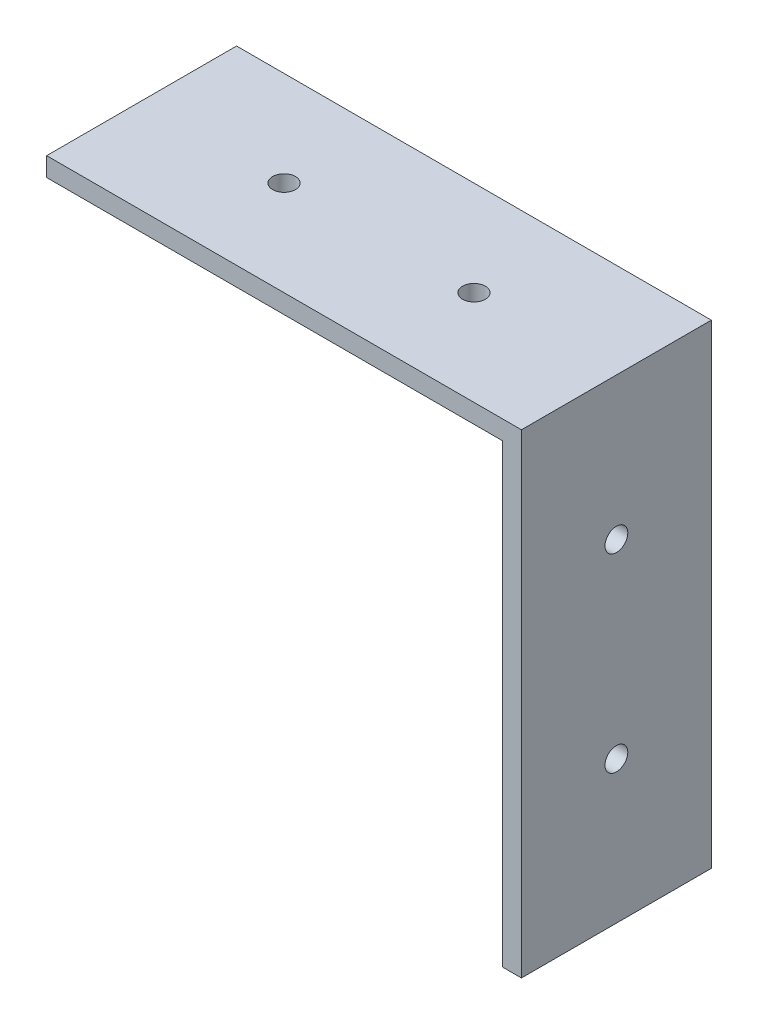
SolidWorks part; units mm, degrees
material "Plain Carbon Steel"
ref_plane "Front Plane" through (0, 0, 0) normal (0, 0, 1) x (1, 0, 0)
ref_plane "Top Plane" through (0, 0, 0) normal (0, 1, 0) x (1, 0, 0)
ref_plane "Right Plane" through (0, 0, 0) normal (1, 0, 0) x (0, 0, -1)
sketch "Sketch1" plane through (0, 0, 0) normal (0, 0, 1) x (1, 0, 0)
  line L0 (-50, 0) -> (-50, -2)
  line L1 (-50, -2) -> (-2, -2)
  line L2 (-2, -2) -> (-2, -50)
  line L3 (-2, -50) -> (0, -50)
  line L4 (0, -50) -> (0, 0)
  line L5 (0, 0) -> (-50, 0)
  dimension "D1" = 2
  dimension "D2" = 50
extrude "Boss-Extrude1" add sketch "Sketch1" along normal blind 20
sketch "Sketch2" plane through (0, 0, 0) normal (0, 1, 0) x (1, 0, 0)
  line L0 (0, -20) -> (0, 0) construction
  point P0 (-35, -10)
  point P1 (-15, -10)
  point P16 (0, -10)
  dimension "D1" = 15
  dimension "D3" = 20
sketch "Sketch3" plane through (0, 0, 0) normal (1, 0, 0) x (0, 0, -1)
  line L0 (-20, 0) -> (0, 0) construction
  point P0 (-10, -15)
  point P1 (-10, -35)
  point P5 (-10, 0)
  dimension "D1" = 15
  dimension "D2" = 20
hole_wizard "M2 Clearance Hole1" positions "3DSketch1" profile "Sketch5" hole size "M2" standard "ANSI Metric"
sketch3d "3DSketch1"
  point P0 (-35, 0, 10)
  point P3 (-15, 0, 10)
  point P7 (0, -15, 10)
  point P10 (0, -35, 10)
sketch "Sketch5" plane through (-35, 0, 10) normal (1, 0, 0) x (0, 0, 1)
  line L0 (0, 0) -> (0, 3.721)
  line L1 (0, 3.721) -> (1.2, 3)
  line L2 (1.2, 3) -> (1.2, 0)
  line L5 (1.2, 0) -> (0, 0)
  line L10 (0, 3.721) -> (-1.2, 3) construction
  line L11 (0, -6.35) -> (0, 107.95) construction
  dimension "Hole Dia." = 2.4
  dimension "Hole Depth" = 3
  dimension "Drill Angle" = 118
